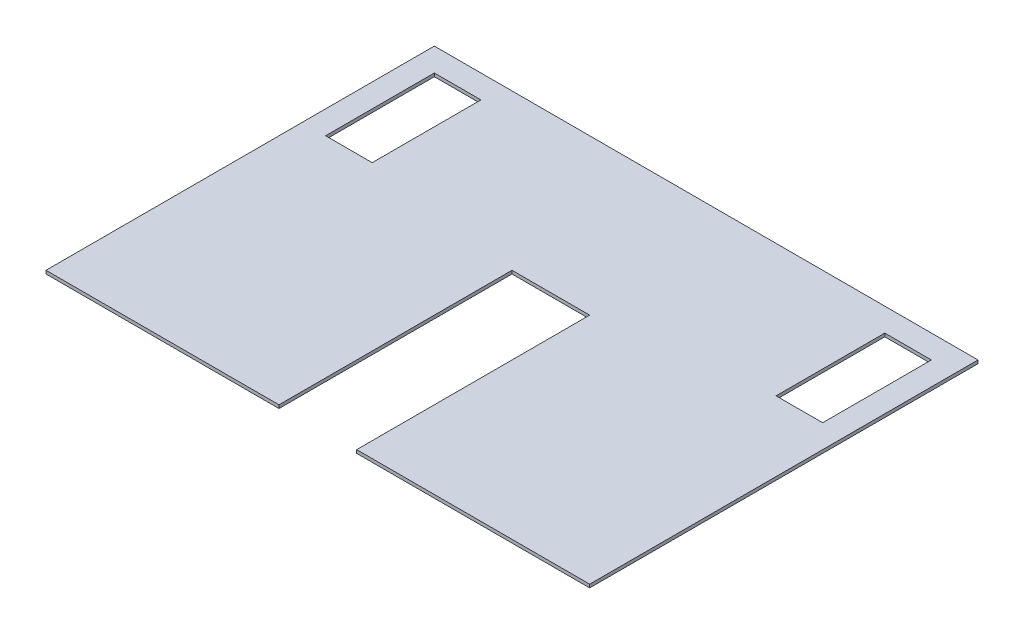
SolidWorks part; units mm, degrees
material "6061-T6 (SS)"
ref_plane "Front" through (0, 0, 0) normal (0, 0, 1) x (1, 0, 0)
ref_plane "Top" through (0, 0, 0) normal (0, 1, 0) x (1, 0, 0)
ref_plane "Right" through (0, 0, 0) normal (1, 0, 0) x (0, 0, -1)
sketch "Sketch1" plane through (0, 0, 0) normal (0, 1, 0) x (1, 0, 0)
  line L1 (0, 0) -> (-177.8, 0)
  line L2 (0, 0) -> (0, 127)
  line L3 (0, 127) -> (-177.8, 127)
  line L4 (-177.8, 0) -> (-177.8, 127)
  dimension "D1" = 177.8
  dimension "D2" = 127
extrude "Boss-Extrude1" add sketch "Sketch1" along normal blind 1.0668
sketch "Sketch2" plane through (0, 1.0668, 0) normal (0, 1, 0) x (1, 0, 0)
  line L0 (-101.6, 82.55) -> (-101.6, 0) construction
  line L1 (-101.6, 76.2) -> (-76.2, 76.2) construction
  line L3 (-76.2, 82.55) -> (-76.2, 0) construction
  line L6 (-177.8, 0) -> (0, 0) construction
  line L10 (-24.13, 127) -> (-24.13, 76.2) construction
  line L15 (-24.13, 82.55) -> (0, 82.55) construction
  line L21 (-6.35, 120.65) -> (-6.35, 82.55) construction
  line L28 (0, 120.65) -> (-24.13, 120.65) construction
  line L36 (-177.8, 82.55) -> (-153.67, 82.55) construction
  line L45 (-171.45, 120.65) -> (-171.45, 82.55) construction
  line L55 (-153.67, 76.2) -> (-153.67, 127) construction
  line L66 (-153.67, 120.65) -> (-177.8, 120.65) construction
  line L78 (-171.45, 120.65) -> (-171.45, 82.55) construction
  line L79 (-171.45, 82.55) -> (-153.67, 82.55) construction
  line L80 (-153.67, 82.55) -> (-153.67, 120.65) construction
  line L81 (-153.67, 120.65) -> (-171.45, 120.65) construction
  line L82 (-101.6, 76.2) -> (-101.6, 0)
  line L83 (-76.2, 76.2) -> (-76.2, 0)
  line L84 (-101.6, 76.2) -> (-76.2, 76.2)
  line L85 (-101.6, 0) -> (-76.2, 0)
  line L86 (-6.35, 120.65) -> (-6.35, 82.55) construction
  line L87 (-24.13, 120.65) -> (-24.13, 82.55) construction
  line L88 (-24.13, 82.55) -> (-6.35, 82.55) construction
  line L89 (-6.35, 120.65) -> (-24.13, 120.65) construction
  line L90 (-170.18, 83.82) -> (-154.94, 83.82)
  line L91 (-154.94, 83.82) -> (-154.94, 119.38)
  line L92 (-154.94, 119.38) -> (-170.18, 119.38)
  line L93 (-170.18, 119.38) -> (-170.18, 83.82)
  line L94 (-22.86, 119.38) -> (-22.86, 83.82)
  line L95 (-22.86, 83.82) -> (-7.62, 83.82)
  line L96 (-7.62, 119.38) -> (-7.62, 83.82)
  line L97 (-7.62, 119.38) -> (-22.86, 119.38)
  dimension "D1" = 1.27
extrude "Cut-Extrude1" cut sketch "Sketch2" against normal through all
